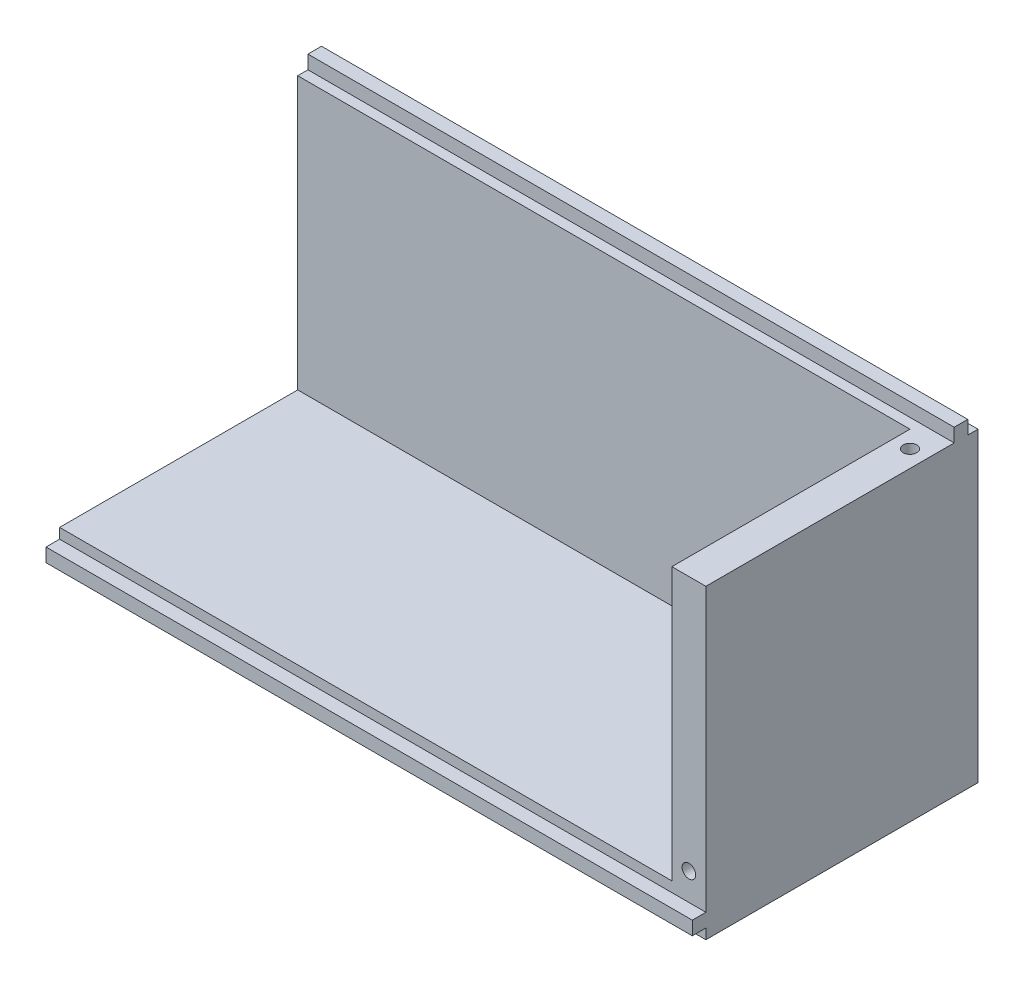
SolidWorks part; units mm, degrees
ref_plane "Alzado" through (0, 0, 0) normal (0, 0, 1) x (1, 0, 0)
ref_plane "Planta" through (0, 0, 0) normal (0, 1, 0) x (1, 0, 0)
ref_plane "Vista lateral" through (0, 0, 0) normal (1, 0, 0) x (0, 0, -1)
sketch "Croquis1" plane through (0, 0, 0) normal (0, 1, 0) x (1, 0, 0)
  line L1 (0, 0) -> (95, 0)
  line L2 (0, 0) -> (0, 40)
  line L3 (0, 40) -> (95, 40)
  line L4 (95, 0) -> (95, 40)
  dimension "D1" = 95
  dimension "D2" = 40
extrude "Saliente-Extruir1" add sketch "Croquis1" along normal blind 5
sketch "Croquis2" plane through (0, 5, 0) normal (0, 1, 0) x (1, 0, 0)
  line L0 (0, 35) -> (90, 35)
  line L1 (0, 40) -> (0, 0) construction
  line L2 (90, 35) -> (90, 0)
  line L3 (0, 0) -> (95, 0) construction
  line L4 (90, 0) -> (95, 0)
  line L5 (95, 0) -> (95, 40)
  line L6 (95, 40) -> (0, 40)
  line L7 (0, 40) -> (0, 35)
  dimension "D1" = 5
  dimension "D2" = 5
extrude "Saliente-Extruir2" add sketch "Croquis2" along normal blind 40
sketch "Croquis3" plane through (0, 45, 0) normal (0, 1, 0) x (1, 0, 0)
  line L0 (0, 40) -> (0, 35) construction
  line L1 (0, 36.5) -> (95, 36.5)
  line L2 (0, 36.5) -> (0, 38.5)
  line L3 (0, 38.5) -> (95, 38.5)
  line L4 (95, 36.5) -> (95, 38.5)
  line L5 (95, 0) -> (95, 40) construction
  line L6 (95, 40) -> (0, 40) construction
  dimension "D1" = 2
  dimension "D2" = 1.5
extrude "Saliente-Extruir3" add sketch "Croquis3" along normal blind 2
sketch "Croquis4" plane through (0, 0, 0) normal (0, 0, 1) x (1, 0, 0)
  line L0 (0, 5) -> (0, 0) construction
  line L1 (0, 1.5) -> (95, 1.5)
  line L2 (0, 1.5) -> (0, 3.5)
  line L3 (0, 3.5) -> (95, 3.5)
  line L4 (95, 1.5) -> (95, 3.5)
  line L5 (95, 45) -> (95, 0) construction
  line L6 (0, 5) -> (90, 5) construction
  dimension "D1" = 2
  dimension "D2" = 1.5
extrude "Saliente-Extruir4" add sketch "Croquis4" along normal blind 2
sketch "Croquis5" plane through (0, 0, 0) normal (-1, 0, 0) x (0, 0, 1)
  line L0 (-35, 5) -> (0, 5) construction
  line L1 (0, 5) -> (0, 3.5) construction
  line L2 (-40, 45) -> (-40, 0) construction
  line L3 (-36.5, 45) -> (-35, 45) construction
  point P0 (-37.5, 42.5)
  point P1 (-2.5, 2.5)
  dimension "D1" = 2.5
  dimension "D2" = 2.5
  dimension "D3" = 2.5
  dimension "D4" = 2.5
hole_wizard "Diámetro de taladro Ø2.0 (2)1" positions "Croquis3D1" profile "Croquis6" hole size "Ø2.0" standard "DIN"
sketch3d "Croquis3D1"
  point P0 (0, 42.5, -37.5)
  point P3 (0, 2.5, -2.5)
sketch "Croquis6" plane through (0, 42.5, -37.5) normal (0, 1, 0) x (0, 0, 1)
  line L0 (0, 0) -> (0, 10.6009)
  line L1 (0, 10.6009) -> (1, 10)
  line L2 (1, 10) -> (1, 0)
  line L5 (1, 0) -> (0, 0)
  line L10 (0, 10.6009) -> (-1, 10) construction
  line L11 (0, -6.35) -> (0, 107.95) construction
  dimension "Diámetro de taladro" = 2
  dimension "Profundidad de taladro" = 10
  dimension "Ángulo de perforador" = 118
sketch "Croquis7" plane through (0, 0, 0) normal (0, 0, 1) x (1, 0, 0)
  line L0 (95, 45) -> (95, 3.5) construction
  line L1 (0, 0) -> (95, 0) construction
  point P0 (92.5, 7.5)
  dimension "D1" = 2.5
  dimension "D2" = 7.5
sketch "Croquis8" plane through (0, 45, 0) normal (0, 1, 0) x (1, 0, 0)
  line L0 (95, 40) -> (0, 40) construction
  line L1 (95, 0) -> (95, 36.5) construction
  point P0 (92.5, 32.5)
  dimension "D1" = 7.5
  dimension "D2" = 2.5
hole_wizard "Diámetro de taladro Ø2.0 (2)2" positions "Croquis3D2" profile "Croquis9" hole size "Ø2.0" standard "DIN"
sketch3d "Croquis3D2"
  point P0 (92.5, 45, -32.5)
  point P3 (92.5, 7.5, 0)
sketch "Croquis9" plane through (92.5, 45, -32.5) normal (1, 0, 0) x (0, 0, 1)
  line L0 (0, 0) -> (0, 10.6009)
  line L1 (0, 10.6009) -> (1, 10)
  line L2 (1, 10) -> (1, 0)
  line L5 (1, 0) -> (0, 0)
  line L10 (0, 10.6009) -> (-1, 10) construction
  line L11 (0, -6.35) -> (0, 107.95) construction
  dimension "Diámetro de taladro" = 2
  dimension "Profundidad de taladro" = 10
  dimension "Ángulo de perforador" = 118
